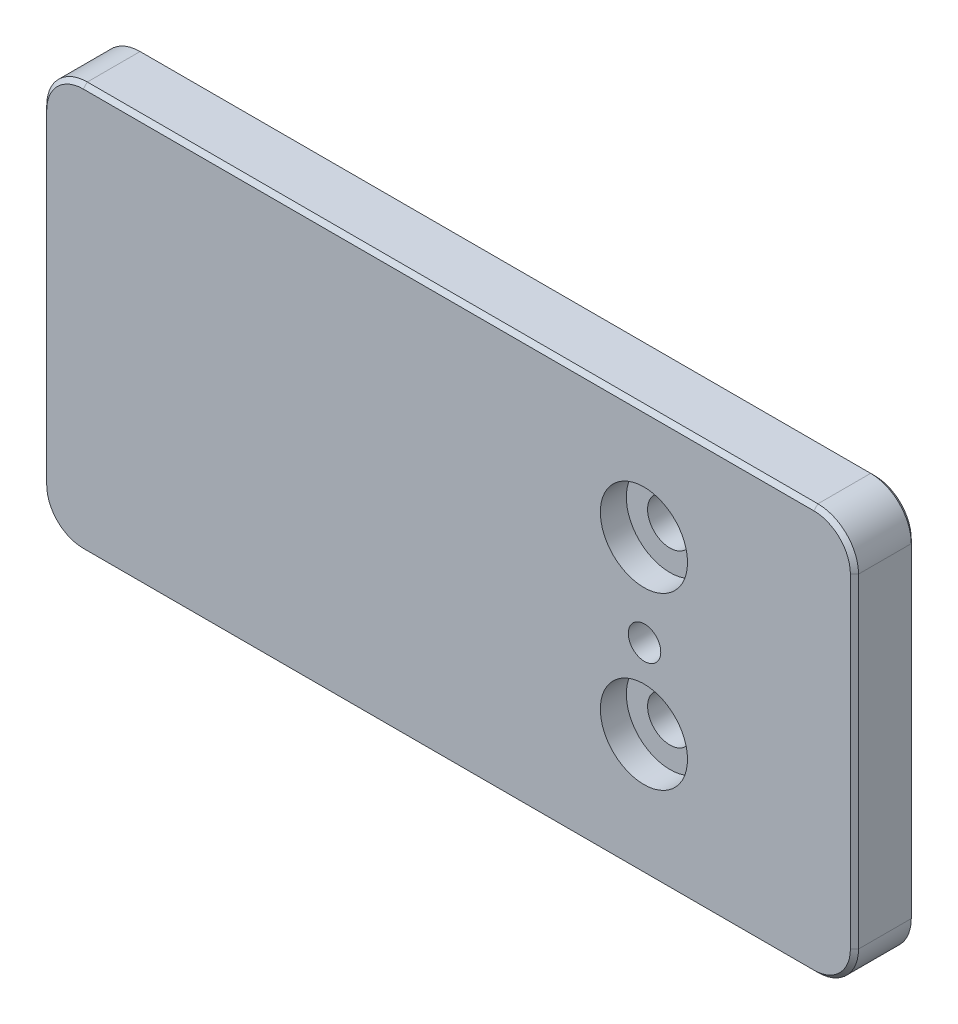
SolidWorks part; units mm, degrees
material "AL5083"
ref_plane "Front Plane" through (0, 0, 0) normal (0, 0, 1) x (1, 0, 0)
ref_plane "Top Plane" through (0, 0, 0) normal (0, 1, 0) x (1, 0, 0)
ref_plane "Right Plane" through (0, 0, 0) normal (1, 0, 0) x (0, 0, -1)
sketch "Sketch1" plane through (0, 0, 0) normal (0, 0, 1) x (1, 0, 0)
  line L1 (-100, 50) -> (100, 50)
  line L2 (-100, 50) -> (-100, -50)
  line L3 (-100, -50) -> (100, -50)
  line L4 (100, 50) -> (100, -50)
  line L5 (-100, 50) -> (100, -50) construction
  line L6 (-100, -50) -> (100, 50) construction
  point P0 (0, 0)
  dimension "D1" = 200
  dimension "D2" = 100
extrude "Boss-Extrude1" add sketch "Sketch1" along normal blind 15
fillet "Fillet1" radius 10 4 edges at (100, 50, 7.5) (100, -50, 7.5) (-100, 50, 7.5) (-100, -50, 7.5)
sketch "Sketch4" plane through (0, 0, 15) normal (0, 0, 1) x (1, 0, 0)
  point P0 (48.1327, 22.4271)
  point P2 (48.1327, -19.5958)
hole_wizard "CBORE for M10 Hex Head Bolt1" positions "Sketch4" profile "Sketch3" counterbore size "M10" standard "DIN" end condition through all
sketch "Sketch3" plane through (48.1327, 22.4271, 15) normal (1, 0, 0) x (0, -1, 0)
  line L0 (0, 0) -> (0, 15)
  line L1 (0, 15) -> (5.5, 15)
  line L3 (5.5, 15) -> (5.5, 6.4)
  line L4 (5.5, 6.4) -> (10.7375, 6.4)
  line L5 (10.7375, 6.4) -> (10.7375, 0)
  line L7 (10.7375, 0) -> (0, 0)
  line L11 (0, -6.35) -> (0, 107.95) construction
  dimension "Thru Hole Dia." = 11
  dimension "Thru Hole Depth" = 15
  dimension "C'Bore Dia." = 21.475
  dimension "C'Bore Depth" = 6.4
sketch "Sketch7" plane through (0, 0, 15) normal (0, 0, 1) x (1, 0, 0)
  point P0 (48.2817, 0)
hole_wizard "Ø8.0mm Dowel Hole1" positions "Sketch7" profile "Sketch6" hole size "Ø8.0" standard "DIN" end condition through all
sketch "Sketch6" plane through (48.2817, 0, 15) normal (1, 0, 0) x (0, -1, 0)
  line L0 (0, 0) -> (0, 15)
  line L1 (0, 15) -> (4, 15)
  line L2 (4, 15) -> (4, 0)
  line L5 (4, 0) -> (0, 0)
  line L11 (0, -6.35) -> (0, 107.95) construction
  dimension "Thru Hole Dia." = 8
  dimension "Thru Hole Depth" = 15
chamfer "Chamfer1" distance 1 angle 45 16 edges at (0, 50, 15) (-97.0711, 47.0711, 15) (97.0711, 47.0711, 15) (-100, 0, 15) (100, 0, 15) (-97.0711, -47.0711, 15) (97.0711, -47.0711, 15) (0, -50, 15) (0, 50, 0) (-97.0711, 47.0711, 0) (97.0711, 47.0711, 0) (-100, 0, 0) (100, 0, 0) (-97.0711, -47.0711, 0) (97.0711, -47.0711, 0) (0, -50, 0)
